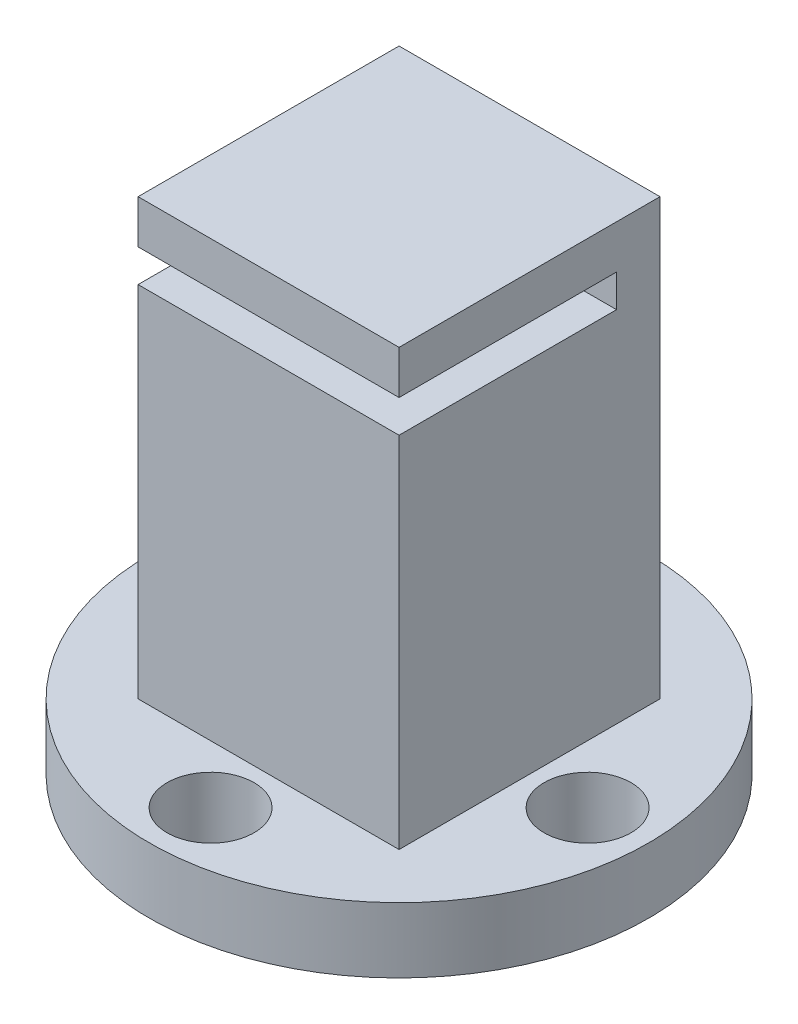
SolidWorks part; units mm, degrees
ref_plane "Alzado" through (0, 0, 0) normal (0, 0, 1) x (1, 0, 0)
ref_plane "Planta" through (0, 0, 0) normal (0, 1, 0) x (1, 0, 0)
ref_plane "Vista lateral" through (0, 0, 0) normal (1, 0, 0) x (0, 0, -1)
sketch "Croquis1" plane through (0, 0, 0) normal (0, 1, 0) x (1, 0, 0)
  line L1 (0, 0) -> (12, 0)
  line L2 (0, 0) -> (0, 12)
  line L3 (0, 12) -> (12, 12)
  line L4 (12, 0) -> (12, 12)
  dimension "D1" = 12
  dimension "D2" = 12
extrude "Saliente-Extruir1" add sketch "Croquis1" along normal blind 20
sketch "Croquis2" plane through (0, 0, 0) normal (0, 0, 1) x (1, 0, 0)
  line L0 (0, 20) -> (0, 0) construction
  line L1 (0, 18) -> (12, 18)
  line L2 (0, 18) -> (0, 16.5)
  line L3 (0, 16.5) -> (12, 16.5)
  line L4 (12, 18) -> (12, 16.5)
  line L5 (0, 20) -> (12, 20) construction
  line L6 (12, 20) -> (12, 0) construction
  dimension "D1" = 1.5
  dimension "D2" = 2
  dimension "D3" = 0
extrude "Cortar-Extruir1" cut sketch "Croquis2" against normal blind 10
sketch "Croquis3" plane through (0, 0, 0) normal (0, -1, 0) x (1, 0, 0)
  line L0 (6, 0) -> (6, -13.845) construction
  line L1 (0, 0) -> (12, 0) construction
  line L2 (0, -6) -> (20.1655, -6) construction
  line L3 (0, -12) -> (0, 0) construction
  circle A0 centre (6, -6) radius 11.4782
  circle A1 centre (14.6685, -6) radius 2
  circle A2 centre (6, -14.6685) radius 2
  circle A3 centre (-2.6685, -6) radius 2
  circle A4 centre (6, 2.6685) radius 2
  point P21 (6, -6)
  dimension "D1" = 4
  dimension "D2" = 4
extrude "Saliente-Extruir2" add sketch "Croquis3" along normal blind 3
